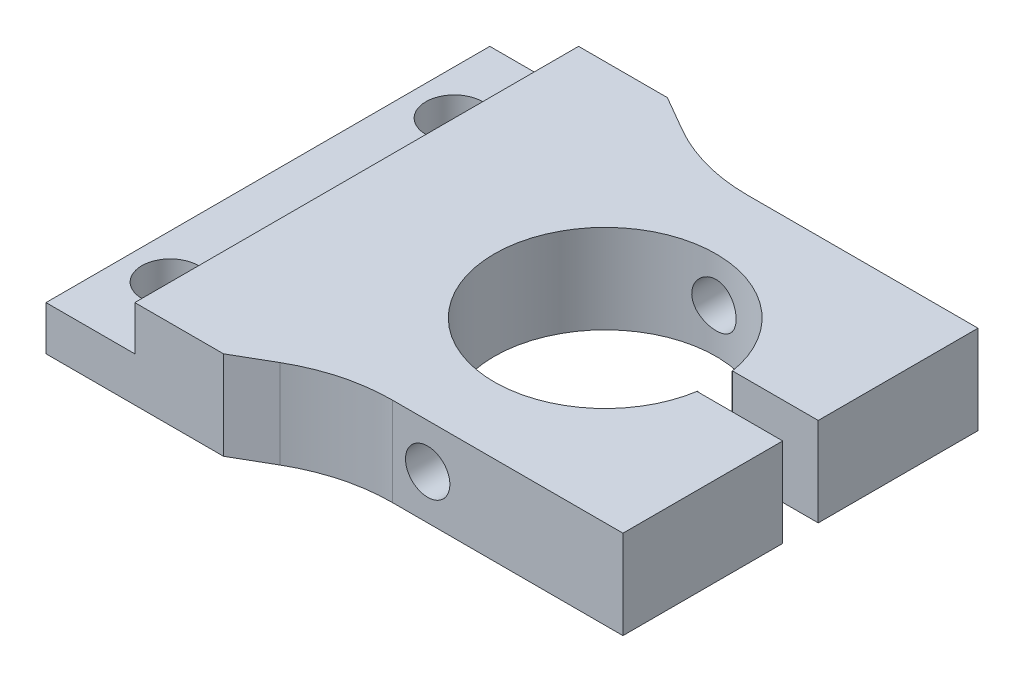
SolidWorks part; units mm, degrees
material "1060 Legierung"
ref_plane "Ebene vorne" through (0, 0, 0) normal (0, 0, 1) x (1, 0, 0)
ref_plane "Ebene oben" through (0, 0, 0) normal (0, 1, 0) x (1, 0, 0)
ref_plane "Ebene rechts" through (0, 0, 0) normal (1, 0, 0) x (0, 0, -1)
sketch "Skizze1" plane through (0, 0, 0) normal (0, 1, 0) x (1, 0, 0)
  line L0 (0, -12.5) -> (0, 12.5)
  line L1 (0, 12.5) -> (30, 12.5)
  line L2 (30, 12.5) -> (30, -12.5)
  line L3 (30, -12.5) -> (0, -12.5)
  point P5 (0, 0)
  dimension "D1" = 25
  dimension "D2" = 30
extrude "Aufsatz-Linear austragen1" add sketch "Skizze1" along normal blind 5
sketch "Skizze2" plane through (0, 5, 0) normal (0, 1, 0) x (1, 0, 0)
  line L0 (0, 12.5) -> (0, -12.5) construction
  line L1 (0, 12.5) -> (5, 12.5)
  line L2 (0, 12.5) -> (0, -12.5)
  line L3 (0, -12.5) -> (5, -12.5)
  line L4 (5, 12.5) -> (5, -12.5)
  line L5 (30, 12.5) -> (0, 12.5) construction
  line L6 (0, -12.5) -> (30, -12.5) construction
  dimension "D1" = 5
extrude "Schnitt-Linear austragen1" cut sketch "Skizze2" against normal blind 2.5
hole_wizard "Ø12.5 (12.5) Durchmesser Bohrung1" positions "Skizze3" profile "Skizze4" hole size "Ø12.5" standard "DIN"
sketch "Skizze3" plane through (0, 5, 0) normal (0, 1, 0) x (1, 0, 0)
  line L0 (5, -12.5) -> (5, 12.5) construction
  point P0 (19, 0)
  dimension "D1" = 14
sketch "Skizze4" plane through (19, 5, 0) normal (1, 0, 0) x (0, 0, 1)
  line L0 (0, 0) -> (0, 8.7554)
  line L1 (0, 8.7554) -> (6.25, 5)
  line L2 (6.25, 5) -> (6.25, 0)
  line L5 (6.25, 0) -> (0, 0)
  line L10 (0, 8.7554) -> (-6.25, 5) construction
  line L11 (0, -6.35) -> (0, 107.95) construction
  dimension "Bohrerdurchmesser" = 12.5
  dimension "Bohrungstiefe" = 5
  dimension "Spitzenwinkel" = 118
hole_wizard "Durchgangsloch für M31" positions "Skizze5" profile "Skizze6" hole size "M3" standard "DIN"
sketch "Skizze5" plane through (0, 0, 0) normal (0, -1, 0) x (-1, 0, 0)
  line L0 (0, 0) -> (-5.2523, 0) construction
  point P0 (-2.5, 8)
  point P4 (-2.5, -8)
  dimension "D1" = 16
  dimension "D2" = 2.5
sketch "Skizze6" plane through (2.5, 0, -8) normal (1, 0, 0) x (0, 0, -1)
  line L0 (0, 0) -> (0, 5.9614)
  line L1 (0, 5.9614) -> (1.6, 5)
  line L2 (1.6, 5) -> (1.6, 0)
  line L5 (1.6, 0) -> (0, 0)
  line L10 (0, 5.9614) -> (-1.6, 5) construction
  line L11 (0, -6.35) -> (0, 107.95) construction
  dimension "Bohrerdurchmesser" = 3.2
  dimension "Bohrungstiefe" = 5
  dimension "Spitzenwinkel" = 118
sketch "Skizze7" plane through (0, 5, 0) normal (0, 1, 0) x (1, 0, 0)
  line L0 (10, 12.5) -> (14.3301, 10)
  line L1 (30, 12.5) -> (5, 12.5) construction
  line L2 (14.3301, 10) -> (30, 10)
  line L3 (30, -12.5) -> (30, 12.5) construction
  line L4 (30, -10) -> (14.3301, -10)
  line L5 (14.3301, -10) -> (10, -12.5)
  line L6 (5, -12.5) -> (30, -12.5) construction
  line L8 (10, 12.5) -> (30, 12.5)
  line L9 (30, 12.5) -> (30, 10)
  line L10 (30, -10) -> (30, -12.5)
  line L11 (30, -12.5) -> (10, -12.5)
  dimension "D1" = 30
  dimension "D2" = 20
  dimension "D3" = 10
  dimension "D4" = 30
extrude "Schnitt-Linear austragen2" cut sketch "Skizze7" against normal through all
sketch "Skizze8" plane through (0, 5, 0) normal (0, 1, 0) x (1, 0, 0)
  line L0 (30, 1) -> (25.1767, 1)
  line L1 (30, -10) -> (30, 10) construction
  line L2 (25.1767, 1) -> (25.1767, -1)
  line L3 (25.1767, -1) -> (30, -1)
  line L4 (30, -1) -> (30, 1)
  point P8 (25.1767, 0)
  dimension "D1" = 2
extrude "Schnitt-Linear austragen3" cut sketch "Skizze8" against normal blind 10
sketch "Skizze9" plane through (0, 0, 10) normal (0, 0, 1) x (1, 0, 0)
  line L0 (30, 0) -> (30, 5) construction
  circle A0 centre (27, 2.5) radius 1.6
  point P5 (30, 2.5)
  dimension "D2" = 3.2
  dimension "D1" = 3
extrude "Schnitt-Linear austragen4" [suppressed] cut sketch "Skizze9" against normal blind 10
hole_wizard "M3 Gewindebohrung1" [suppressed] positions "Skizze10" profile "Skizze11" tap size "M3" standard "DIN"
sketch "Skizze10" [suppressed] plane through (0, 0, -1) normal (0, 0, 1) x (1, 0, 0)
  circle A0 centre (27, 2.5) radius 1.6 construction
  point P0 (27, 2.5)
sketch "Skizze11" plane through (27, 2.5, -1) normal (1, 0, 0) x (0, -1, 0)
  line L0 (0, 0) -> (0, 8.7511)
  line L1 (0, 8.7511) -> (1.25, 8)
  line L2 (1.25, 8) -> (1.25, 0)
  line L5 (1.25, 0) -> (0, 0)
  line L10 (0, 8.7511) -> (-1.25, 8) construction
  line L11 (0, -6.35) -> (0, 107.95) construction
  dimension "Bohrerdurchmesser" = 2.5
  dimension "Bohrungstiefe" = 8
  dimension "Spitzenwinkel" = 118
cosmetic thread "Bohrungsgewinde1" [suppressed] parameters "D1"=6, "D2"=3
fillet "Verrundung1" radius 10 2 edges at (14.3301, 2.5, 10) (14.3301, 2.5, -10)
hole_wizard "M3 Gewindebohrung2" positions "Skizze12" profile "Skizze13" tap size "M3" standard "DIN" end condition through all
sketch "Skizze12" plane through (0, 0, 10) normal (0, 0, 1) x (1, 0, 0)
  line L0 (30, 2.5) -> (17.0096, 2.5) construction
  line L1 (30, 0) -> (30, 5) construction
  line L2 (17.0096, 5) -> (17.0096, 0) construction
  line L5 (5, 2.5) -> (5, 5) construction
  point P0 (19, 2.5)
  dimension "D1" = 14
sketch "Skizze13" plane through (19, 2.5, 10) normal (1, 0, 0) x (0, -1, 0)
  line L0 (0, 0) -> (0, 22.5)
  line L1 (0, 22.5) -> (1.25, 22.5)
  line L2 (1.25, 22.5) -> (1.25, 0)
  line L5 (1.25, 0) -> (0, 0)
  line L11 (0, -6.35) -> (0, 107.95) construction
  dimension "Bohrerdurchmesser" = 2.5
  dimension "Bohrungstiefe" = 22.5
cosmetic thread "Bohrungsgewinde2" parameters "D2"=3
